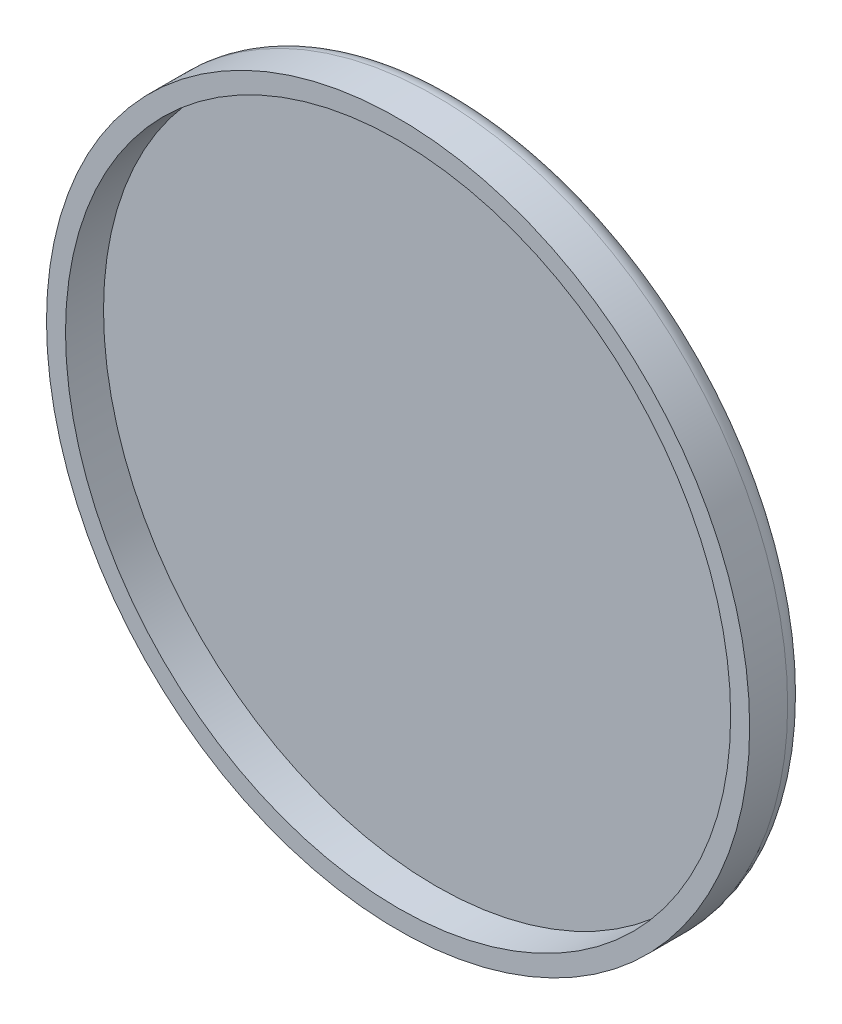
SolidWorks part; units mm, degrees
ref_plane "Plan de face" through (0, 0, 0) normal (0, 0, 1) x (1, 0, 0)
ref_plane "Plan de dessus" through (0, 0, 0) normal (0, 1, 0) x (1, 0, 0)
ref_plane "Plan de droite" through (0, 0, 0) normal (1, 0, 0) x (0, 0, -1)
sketch "Esquisse1" plane through (0, 0, 0) normal (0, 0, 1) x (1, 0, 0)
  circle A0 centre (0, 0) radius 37
  dimension "D1" = 74
extrude "Boss.-Extru.1" add sketch "Esquisse1" along normal blind 6
sketch "Esquisse2" plane through (0, 0, 6) normal (0, 0, 1) x (1, 0, 0)
  circle A0 centre (0, 0) radius 35
  dimension "D1" = 70
extrude "Enlèv. mat.-Extru.1" cut sketch "Esquisse2" against normal blind 4
fillet "Congé1" radius 2 1 edges at (37, 0, 0)
